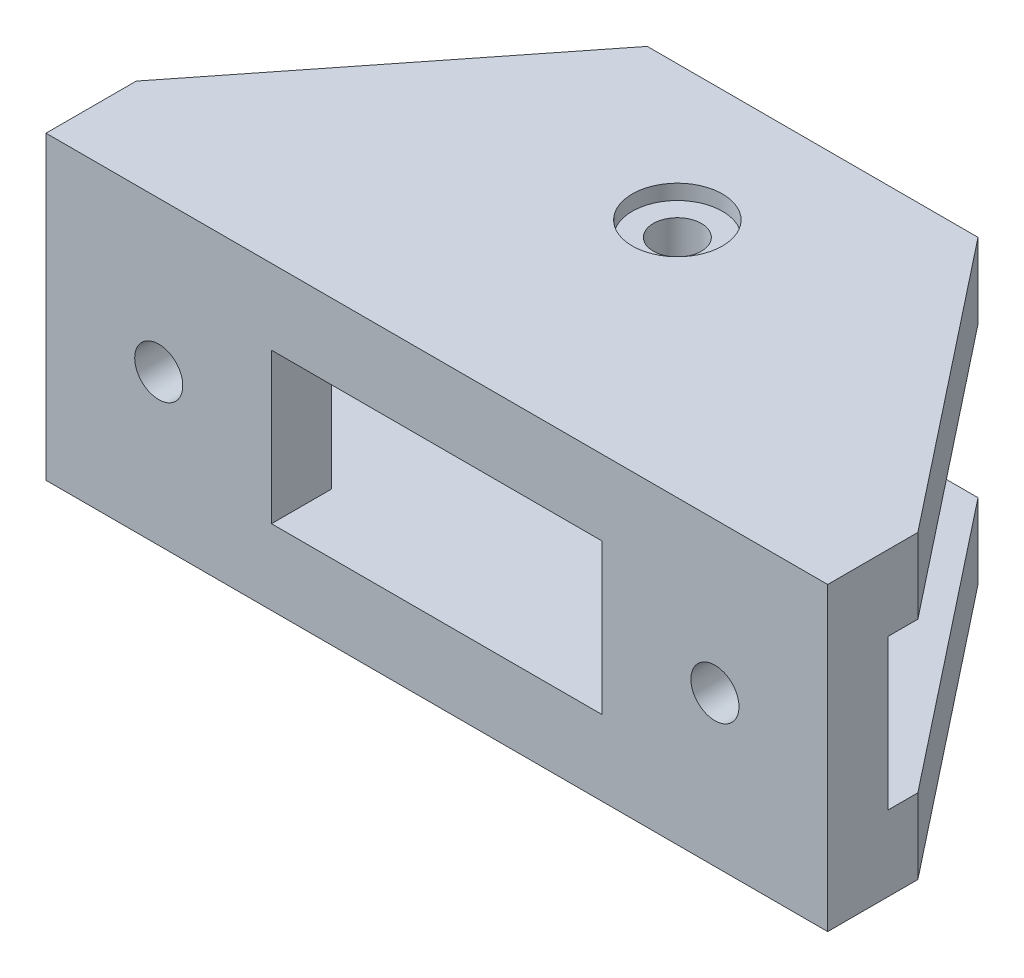
SolidWorks part; units mm, degrees
ref_plane "Front Plane" through (0, 0, 0) normal (0, 0, 1) x (1, 0, 0)
ref_plane "Top Plane" through (0, 0, 0) normal (0, 1, 0) x (1, 0, 0)
ref_plane "Right Plane" through (0, 0, 0) normal (1, 0, 0) x (0, 0, -1)
sketch "Sketch1" plane through (0, 0, 0) normal (0, 0, 1) x (1, 0, 0)
  line L1 (540.5303, 140.4701) -> (488.5303, 140.4701)
  line L2 (540.5303, 140.4701) -> (540.5303, 120.4701)
  line L3 (540.5303, 120.4701) -> (488.5303, 120.4701)
  line L4 (488.5303, 140.4701) -> (488.5303, 120.4701)
  dimension "D1" = 52
  dimension "D2" = 20
extrude "Boss-Extrude1" add sketch "Sketch1" along normal blind 25
sketch "Sketch2" plane through (540.5303, 0, 0) normal (1, 0, 0) x (0, 0, -1)
  line L0 (0, 120.4701) -> (0, 140.4701) construction
  line L1 (0, 135.4701) -> (-21, 135.4701)
  line L2 (0, 135.4701) -> (0, 125.4701)
  line L3 (0, 125.4701) -> (-21, 125.4701)
  line L4 (-21, 135.4701) -> (-21, 125.4701)
  line L5 (-25, 140.4701) -> (0, 140.4701) construction
  line L6 (-25, 120.4701) -> (-25, 140.4701) construction
  dimension "D1" = 5
  dimension "D2" = 15
  dimension "D3" = 4
extrude "Cut-Extrude1" cut sketch "Sketch2" against normal through all
sketch "Sketch3" plane through (0, 140.4701, 0) normal (0, 1, 0) x (1, 0, 0)
  line L0 (488.5303, -19) -> (503.5303, 0)
  line L1 (488.5303, -25) -> (488.5303, 0) construction
  line L2 (540.5303, 0) -> (488.5303, 0) construction
  line L3 (503.5303, 0) -> (525.5303, 0)
  line L4 (525.5303, 0) -> (540.5303, -19)
  line L5 (540.5303, -25) -> (540.5303, 0) construction
  line L6 (540.5303, -19) -> (550.0003, -19)
  line L7 (550.0003, -19) -> (550.0003, 5.4233)
  line L8 (550.0003, 5.4233) -> (484.2775, 5.4233)
  line L9 (484.2775, 5.4233) -> (484.2775, -19)
  line L10 (484.2775, -19) -> (488.5303, -19)
  line L11 (540.5303, -25) -> (488.5303, -25) construction
  dimension "D1" = 6
  dimension "D2" = 6
  dimension "D3" = 15
  dimension "D4" = 15
extrude "Cut-Extrude2" cut sketch "Sketch3" against normal through all
sketch "Sketch4" plane through (0, 140.4701, 0) normal (0, 1, 0) x (1, 0, 0)
  line L0 (525.5303, 0) -> (503.5303, 0) construction
  circle A0 centre (514.5303, -9) radius 1.6
  dimension "D1" = 3.2
  dimension "D2" = 9
extrude "Cut-Extrude3" cut sketch "Sketch4" against normal through all
sketch "Sketch5" plane through (0, 0, 21) normal (0, 0, -1) x (-1, 0, 0)
  line L0 (-525.5303, 135.4701) -> (-540.5303, 135.4701) construction
  line L1 (-525.5303, 135.4701) -> (-503.5303, 135.4701)
  line L2 (-525.5303, 135.4701) -> (-525.5303, 125.4701)
  line L3 (-525.5303, 125.4701) -> (-503.5303, 125.4701)
  line L4 (-503.5303, 135.4701) -> (-503.5303, 125.4701)
  line L5 (-503.5303, 125.4701) -> (-488.5303, 125.4701) construction
  line L6 (-540.5303, 135.4701) -> (-540.5303, 125.4701) construction
  line L7 (-488.5303, 135.4701) -> (-488.5303, 125.4701) construction
  dimension "D1" = 15
  dimension "D2" = 15
extrude "Cut-Extrude4" cut sketch "Sketch5" against normal blind 4
sketch "Sketch6" plane through (0, 0, 21) normal (0, 0, -1) x (-1, 0, 0)
  line L0 (-525.5303, 135.4701) -> (-540.5303, 135.4701) construction
  line L1 (-488.5303, 135.4701) -> (-503.5303, 135.4701) construction
  line L2 (-540.5303, 135.4701) -> (-540.5303, 125.4701) construction
  line L3 (-488.5303, 135.4701) -> (-488.5303, 125.4701) construction
  circle A0 centre (-533.0303, 130.4701) radius 1.6
  circle A1 centre (-496.0303, 130.4701) radius 1.6
  dimension "D1" = 3.2
  dimension "D2" = 3.2
  dimension "D3" = 5
  dimension "D4" = 5
  dimension "D5" = 7.5
  dimension "D6" = 7.5
extrude "Cut-Extrude5" cut sketch "Sketch6" against normal blind 4
sketch "Sketch7" plane through (0, 0, 21) normal (0, 0, -1) x (-1, 0, 0)
  line L0 (-488.5303, 135.4701) -> (-488.5303, 125.4701) construction
  line L1 (-499.0303, 133.9701) -> (-493.0303, 133.9701)
  line L2 (-499.0303, 133.9701) -> (-499.0303, 126.9701)
  line L3 (-499.0303, 126.9701) -> (-493.0303, 126.9701)
  line L4 (-493.0303, 133.9701) -> (-493.0303, 126.9701)
  line L5 (-503.5303, 125.4701) -> (-488.5303, 125.4701) construction
  dimension "D1" = 6
  dimension "D2" = 7
  dimension "D3" = 4.5
  dimension "D4" = 1.5
extrude "Cut-Extrude6" cut sketch "Sketch7" against normal blind 1
sketch "Sketch8" plane through (0, 0, 21) normal (0, 0, -1) x (-1, 0, 0)
  line L0 (-540.5303, 125.4701) -> (-525.5303, 125.4701) construction
  line L1 (-536.0303, 133.9701) -> (-530.0303, 133.9701)
  line L2 (-536.0303, 133.9701) -> (-536.0303, 126.9701)
  line L3 (-536.0303, 126.9701) -> (-530.0303, 126.9701)
  line L4 (-530.0303, 133.9701) -> (-530.0303, 126.9701)
  line L5 (-540.5303, 135.4701) -> (-540.5303, 125.4701) construction
  dimension "D1" = 6
  dimension "D2" = 7
  dimension "D3" = 1.5
  dimension "D4" = 4.5
extrude "Cut-Extrude7" cut sketch "Sketch8" against normal blind 1
sketch "Sketch9" plane through (0, 140.4701, 0) normal (0, 1, 0) x (1, 0, 0)
  circle A0 centre (514.5303, -9) radius 3
  dimension "D1" = 6
extrude "Cut-Extrude8" cut sketch "Sketch9" against normal blind 1
